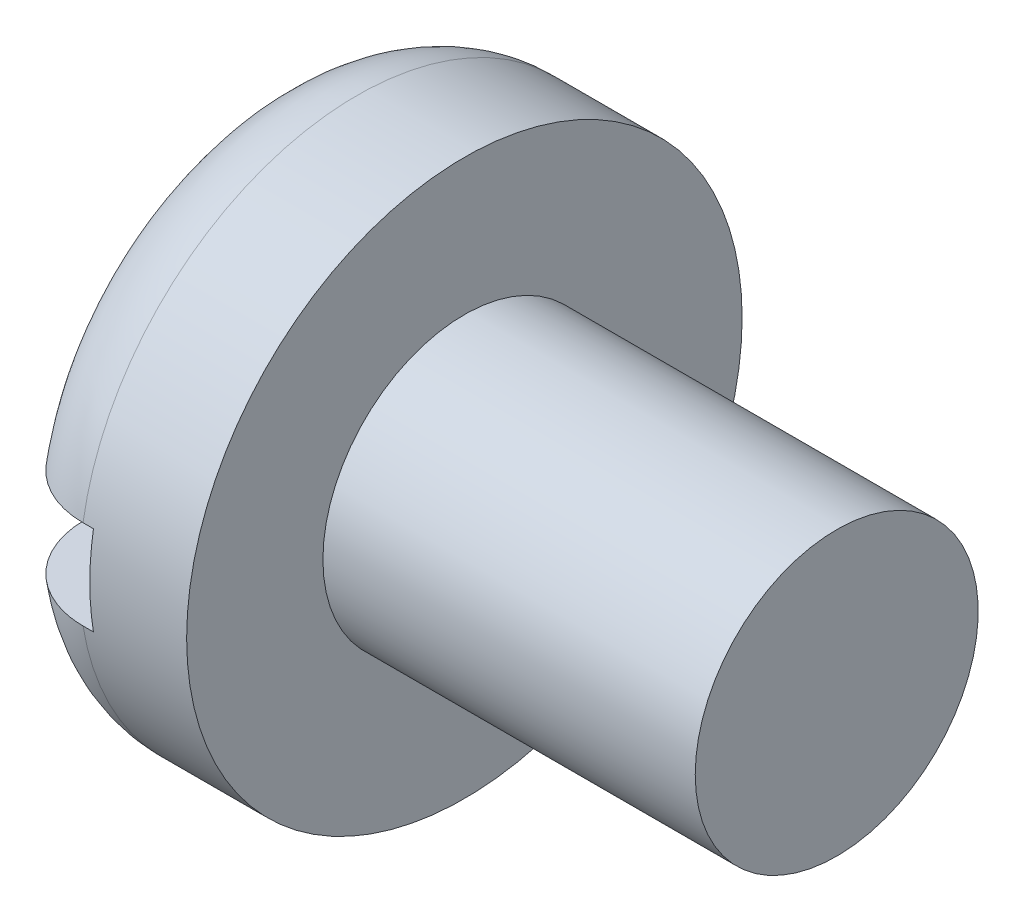
SolidWorks part; units mm, degrees
ref_plane "Plane1" through (0, 0, 0) normal (0, 0, 1) x (1, 0, 0)
ref_plane "Plane2" through (0, 0, 0) normal (0, 1, 0) x (1, 0, 0)
ref_plane "Plane3" through (0, 0, 0) normal (1, 0, 0) x (0, 0, -1)
sketch "BodySke" plane through (0, 0, 0) normal (0, 0, 1) x (1, 0, 0)
  line L0 (3.3782, 2.413) -> (3.3782, 4.7371)
  line L1 (0, 0) -> (0, 3.1877)
  line L2 (-25.4, 0) -> (127, 0) construction
  line L3 (9.7282, 0) -> (0, 0)
  line L4 (3.3782, 2.413) -> (9.7282, 2.413)
  line L5 (9.7282, 2.413) -> (9.7282, 0)
  line L6 (1.5494, 4.7371) -> (3.3782, 4.7371)
  line L7 (3.3782, -2.413) -> (9.7282, -2.413) construction
  line L8 (0, -4.7371) -> (3.3782, -4.7371) construction
  line L9 (4.4374, 4.0005) -> (4.4374, -5.5245) construction
  line L10 (3.3782, 6.35) -> (3.3782, -3.175) construction
  arc A0 (0, 3.1877) -> (1.5494, 4.7371) centre (1.5494, 3.1877) cw
  point P15 (0, 4.7371)
revolve "Base-Revolve" add sketch "BodySke" angle 360 about L2
cosmetic thread "ThreadCosmetic" [suppressed] parameters "Thread_length"=4.0691, "Thread_minor"=3.5662
sketch "Sketch2" plane through (0, 0, 0) normal (1, 0, 0) x (0, 0, -1)
  line L0 (4.7371, -0.762) -> (-4.7371, -0.762)
  line L1 (4.7371, -0.762) -> (4.7371, 0.762)
  line L2 (-4.7371, 0.762) -> (4.7371, 0.762)
  line L3 (-4.7371, 0.762) -> (-4.7371, -0.762)
  dimension "D1" = 8.1788
  dimension "D2" = 4.0894
  dimension "D3" = 0.6858
extrude "Slot" cut sketch "Sketch2" along normal blind 1.7272
sketch "ThdSchSke" plane through (0, 0, 0) normal (0, 0, 1) x (1, 0, 0)
  line L0 (4.4374, -1.7831) -> (3.9963, -2.413)
  line L1 (4.4374, -1.7831) -> (4.8785, -2.413)
  line L2 (4.8785, -2.413) -> (4.8785, -3.0162)
  line L3 (-3.175, 0) -> (5.1513, 0) construction
  line L5 (4.8785, -3.0162) -> (3.9963, -3.0162)
  line L6 (3.9963, -3.0162) -> (3.9963, -2.413)
  dimension "SideAngle" = 55
  dimension "VeeAngle" = 70
  dimension "Thread_minor" = 3.3249
  dimension "Overcut" = 5.207
  dimension "Diameter" = 4.1656
  dimension "Start" = 3.6271
revolve "ThreadSchematic" [suppressed] cut sketch "ThdSchSke" angle 360 about L3
pattern_linear "ThdSchPat" [suppressed]
equation "\"D1@Sketch2\" = \"Head_dia@BodySke\""
equation "\"D2@Sketch2\" = \"D1@Sketch2\" / 2"
equation "\"D3@Sketch2\" = \"Slot_width@Sketch2\" / 2"
equation "\"Thread_length@ThreadCosmetic\" = ((sgn( (\"Length@BodySke\" - \"Advance@BodySke\" ) - \"Thread_nom@BodySke\" )-1)*( (\"Length@BodySke\" - \"Advance@BodySke\" ) - \"Thread_nom@BodySke\" ))/-2+ \"Thread_nom@BodySke\""
equation "\"Thread_minor@ThdSchSke\" = \"Thread_minor@ThreadCosmetic\""
equation "\"Diameter@ThdSchSke\" = \"Diameter@BodySke\""
equation "\"Overcut@ThdSchSke\" = \"Diameter@BodySke\" * 1.25"
equation "\"Start@ThdSchSke\" = \"Head_ht@BodySke\" + \"Length@BodySke\" - \"Thread_length@ThreadCosmetic\"  '---Non-countersunk---"
equation "\"Num_threads@ThdSchPat\" = int( \"Thread_length@ThreadCosmetic\" / \"Advance@BodySke\" + 0.999 )  + 1"
equation "\"Advance@ThdSchPat\" = \"Thread_length@ThreadCosmetic\" /  (\"Num_threads@ThdSchPat\" - 1) 'relax it"
